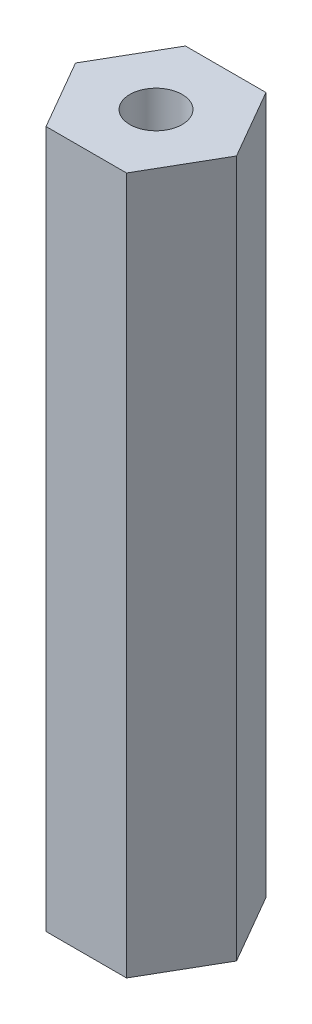
SolidWorks part; units mm, degrees
ref_plane "Front Plane" through (0, 0, 0) normal (0, 0, 1) x (1, 0, 0)
ref_plane "Top Plane" through (0, 0, 0) normal (0, 1, 0) x (1, 0, 0)
ref_plane "Right Plane" through (0, 0, 0) normal (1, 0, 0) x (0, 0, -1)
sketch "Sketch2" plane through (0, 0, 0) normal (0, 1, 0) x (1, 0, 0)
  line L1 (6.9282, 0) -> (3.4641, 6)
  line L2 (3.4641, 6) -> (-3.4641, 6)
  line L3 (-3.4641, 6) -> (-6.9282, 0)
  line L4 (-6.9282, 0) -> (-3.4641, -6)
  line L5 (-3.4641, -6) -> (3.4641, -6)
  line L6 (3.4641, -6) -> (6.9282, 0)
  circle A0 centre (0, 0) radius 6 construction
  dimension "D1" = 12
extrude "Boss-Extrude1" add sketch "Sketch2" along normal blind 60
sketch "Sketch3" plane through (0, 0, 0) normal (0, 1, 0) x (1, 0, 0)
  circle A0 centre (0, 0) radius 2.25
  dimension "D1" = 4.5
extrude "Cut-Extrude1" cut sketch "Sketch3" along normal through all
